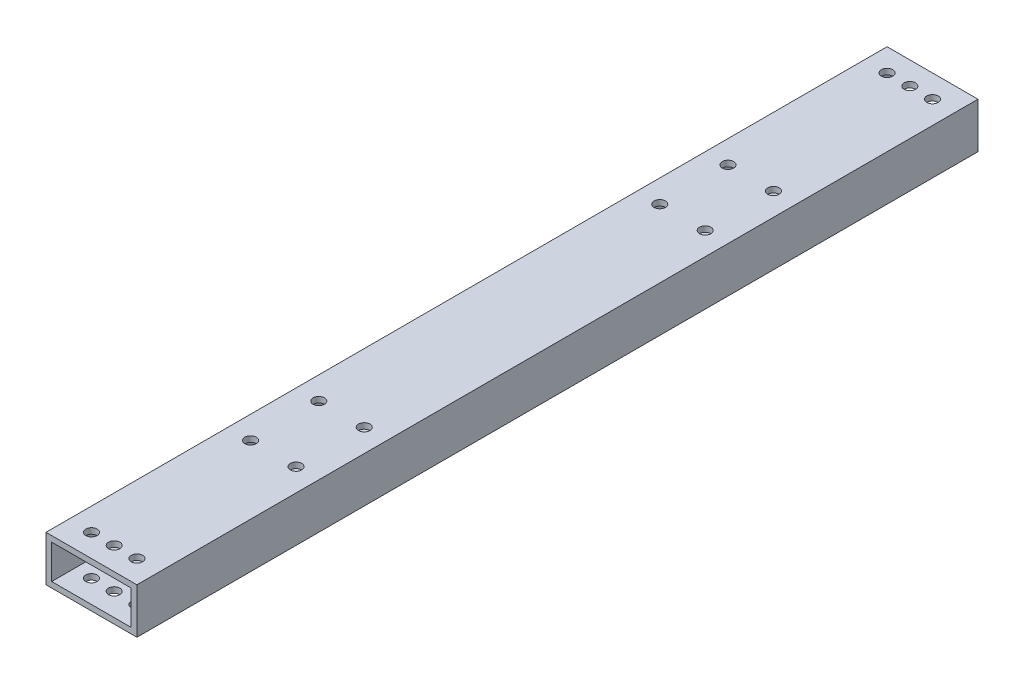
SolidWorks part; units mm, degrees
ref_plane "Front Plane" through (0, 0, 0) normal (0, 0, 1) x (1, 0, 0)
ref_plane "Top Plane" through (0, 0, 0) normal (0, 1, 0) x (1, 0, 0)
ref_plane "Right Plane" through (0, 0, 0) normal (1, 0, 0) x (0, 0, -1)
sketch "Sketch1" plane through (0, 0, 0) normal (0, 0, 1) x (1, 0, 0)
  line L0 (3.175, 22.225) -> (47.625, 22.225)
  line L1 (0, 0) -> (50.8, 0)
  line L2 (0, 0) -> (0, 25.4)
  line L3 (0, 25.4) -> (50.8, 25.4)
  line L4 (50.8, 0) -> (50.8, 25.4)
  line L5 (47.625, 3.175) -> (47.625, 22.225)
  line L6 (3.175, 3.175) -> (47.625, 3.175)
  line L7 (3.175, 3.175) -> (3.175, 22.225)
  dimension "D1" = 25.4
  dimension "D2" = 50.8
  dimension "D3" = 3.175
extrude "Boss-Extrude1" add sketch "Sketch1" along normal blind 469.9
sketch "Sketch3" plane through (0, 25.4, 0) normal (0, 1, 0) x (1, 0, 0)
  line L0 (12.7, -457.2) -> (12.7, -469.9) construction
  line L1 (50.8, -469.9) -> (0, -469.9) construction
  line L2 (12.7, -457.2) -> (0, -457.2) construction
  line L3 (0, -469.9) -> (0, 0) construction
  line L4 (12.7, -12.7) -> (12.7, 0) construction
  line L5 (50.8, 0) -> (0, 0) construction
  line L6 (12.7, -12.7) -> (0, -12.7) construction
  circle A0 centre (12.7, -12.7) radius 3.175
  circle A1 centre (12.7, -457.2) radius 3.175
  circle A2 centre (25.4, -457.2) radius 3.175
  circle A3 centre (25.4, -12.7) radius 3.175
  circle A4 centre (38.1, -457.2) radius 3.175
  circle A5 centre (38.1, -12.7) radius 3.175
  dimension "D2" = 6.35
  dimension "D1" = 12.7
  dimension "D3" = 12.7
extrude "Cut-Extrude1" cut sketch "Sketch3" against normal through all both
sketch "Sketch4" plane through (0, 25.4, 0) normal (0, 1, 0) x (1, 0, 0)
  line L0 (0, -234.95) -> (12.7, -234.95) construction
  line L1 (0, -469.9) -> (0, 0) construction
  line L2 (12.7, -234.95) -> (12.7, -139.7) construction
  line L3 (12.7, -234.95) -> (12.7, -330.2) construction
  line L4 (12.7, -139.7) -> (12.7, -101.6) construction
  line L5 (12.7, -330.2) -> (12.7, -368.3) construction
  line L6 (25.4, 0) -> (25.4, -469.9) construction
  line L7 (50.8, 0) -> (0, 0) construction
  line L8 (50.8, -469.9) -> (0, -469.9) construction
  circle A1 centre (12.7, -139.7) radius 3.175
  circle A2 centre (12.7, -330.2) radius 3.175
  circle A3 centre (12.7, -101.6) radius 3.175
  circle A4 centre (12.7, -368.3) radius 3.175
  circle A5 centre (38.1, -101.6) radius 3.175
  circle A6 centre (38.1, -139.7) radius 3.175
  circle A7 centre (38.1, -330.2) radius 3.175
  circle A8 centre (38.1, -368.3) radius 3.175
  dimension "D2" = 95.25
  dimension "D3" = 6.35
  dimension "D1" = 12.7
  dimension "D4" = 38.1
extrude "Cut-Extrude2" cut sketch "Sketch4" against normal through all both and the other way through all
